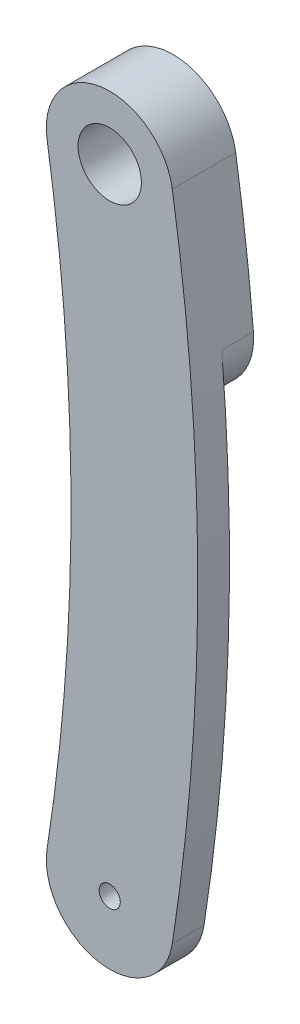
SolidWorks part; units mm, degrees
ref_plane "Front Plane" through (0, 0, 0) normal (0, 0, 1) x (1, 0, 0)
ref_plane "Top Plane" through (0, 0, 0) normal (0, 1, 0) x (1, 0, 0)
ref_plane "Right Plane" through (0, 0, 0) normal (1, 0, 0) x (0, 0, -1)
sketch "Sketch1" plane through (0, 0, 0) normal (0, 0, 1) x (1, 0, 0)
  line L0 (0, 0) -> (39.7718, 0) construction
  arc A0 (2.9639, 15.4639) -> (2.9639, -15.4639) centre (-95.8332, 0) cw
  arc A1 (-2.9639, 14.5361) -> (-2.9639, -14.5361) centre (-95.8332, 0) cw
  arc A2 (2.9639, 15.4639) -> (-2.9639, 14.5361) centre (0, 15) ccw
  arc A3 (2.9639, -15.4639) -> (-2.9639, -14.5361) centre (0, -15) cw
  circle A4 centre (0, 15) radius 1.5
  circle A5 centre (0, -15) radius 0.5
  dimension "D2" = 36
  dimension "D3" = 100
  dimension "D4" = 1
  dimension "D5" = 3
  dimension "D1" = 6
extrude "Boss-Extrude1" add sketch "Sketch1" along normal blind 1.5
sketch "Sketch2" plane through (0, 0, 0) normal (0, 0, -1) x (-1, 0, 0)
  arc A0 (-3.8018, 8.5361) -> (2.1763, 8.0239) centre (-0.8128, 8.28) ccw
  circle A1 centre (0, -15) radius 0.5
  circle A2 centre (0, -15) radius 0.5
  circle A3 centre (0, 15) radius 1.5
  circle A4 centre (0, 15) radius 1.5
  arc A8 (-2.9639, 15.4639) -> (-2.9639, -15.4639) centre (95.8332, 0) ccw
  arc A9 (-2.9639, -15.4639) -> (2.9639, -14.5361) centre (0, -15) ccw
  arc A10 (2.9639, 14.5361) -> (2.9639, -14.5361) centre (95.8332, 0) ccw
  arc A11 (2.9639, 14.5361) -> (-2.9639, 15.4639) centre (0, 15) ccw
  arc A12 (-2.9639, 15.4639) -> (-2.9639, -15.4639) centre (95.8332, 0) ccw
  arc A13 (-2.9639, -15.4639) -> (2.9639, -14.5361) centre (0, -15) ccw
  arc A14 (2.9639, 14.5361) -> (2.9639, -14.5361) centre (95.8332, 0) ccw
  arc A15 (2.9639, 14.5361) -> (-2.9639, 15.4639) centre (0, 15) ccw
  arc M7 (2.9639, 14.5361) -> (-2.9639, 15.4639) centre (0, 15) ccw
  arc M8 (-2.9639, 15.4639) -> (-2.9639, -15.4639) centre (95.8332, 0) ccw
  arc M10 (2.9639, -14.5361) -> (2.9639, 14.5361) centre (95.8332, 0) cw
  circle M12 centre (0, 15) radius 1.5
  dimension "D4" = 24
  dimension "D1" = 0
  dimension "D2" = 0
  dimension "D3" = 0
extrude "Boss-Extrude2" add sketch "Sketch2" along normal blind 1.5 contours A0 M8 M10 M7 M12
